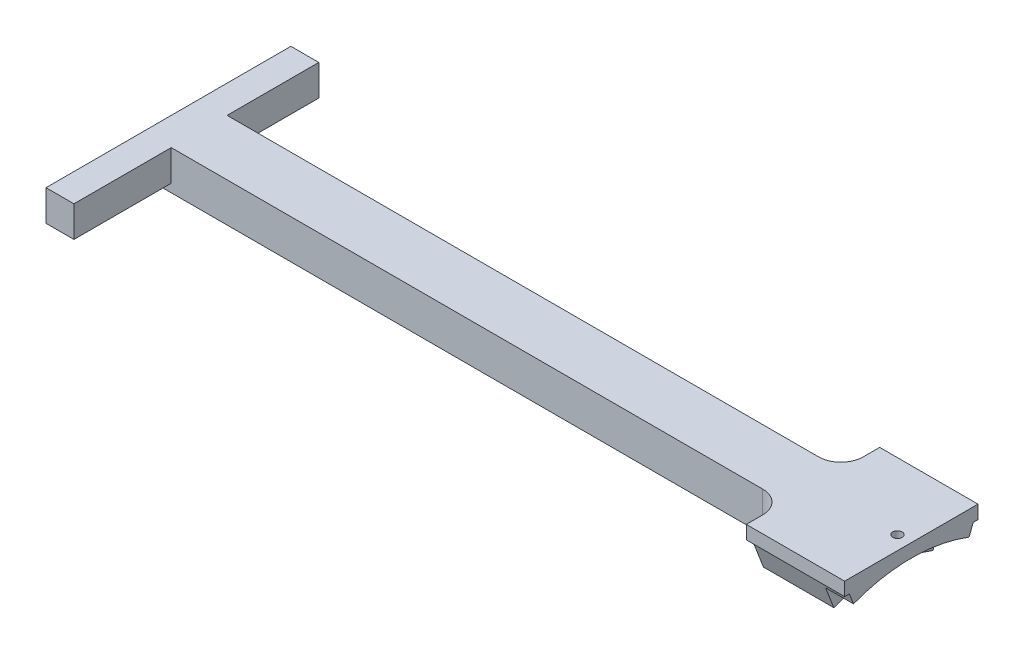
SolidWorks part; units mm, degrees
ref_plane "前视基准面" through (0, 0, 0) normal (0, 0, 1) x (1, 0, 0)
ref_plane "上视基准面" through (0, 0, 0) normal (0, 1, 0) x (1, 0, 0)
ref_plane "右视基准面" through (0, 0, 0) normal (1, 0, 0) x (0, 0, -1)
other "Configuration Table"
sketch "草图2" plane through (-10, 0, 0) normal (-1, 0, 0) x (0, 0, 1)
  line L0 (0, 0) -> (-20.629, 53.5702) construction
  line L2 (20.629, 53.5702) -> (0, 0) construction
  line L3 (0, 0) -> (0, 57.4049) construction
  arc A1 (20.629, 53.5702) -> (-20.629, 53.5702) centre (0, 0) ccw
  circle A2 centre (0, 0) radius 57.4049 construction
extrude "拉伸-薄壁1" add sketch "草图2" along normal blind 10 thin
sketch "草图3" plane through (-10, 0, 0) normal (1, 0, 0) x (0, 0, -1)
  arc A0 (22.4258, 58.2362) -> (-22.4258, 58.2362) centre (0, 0) ccw construction
  arc A1 (22.4258, 58.2362) -> (-22.4258, 58.2362) centre (0, 0) ccw
extrude "拉伸-薄壁2" add sketch "草图3" along normal blind 10 thin thin type one direction reverse wall 4.8
sketch "草图5" plane through (0, 0, 0) normal (1, 0, 0) x (0, 0, -1)
  line L0 (-23.8803, 62.4049) -> (23.8803, 62.4049)
  line L1 (0, 0) -> (0, 67.8698) construction
  arc A0 (22.4258, 58.2362) -> (-22.4258, 58.2362) centre (0, 0) ccw construction
extrude "拉伸-薄壁3" add sketch "草图5" against normal up to surface (20 mm away) thin
sketch "草图4" plane through (0, 0, 0) normal (0, 1, 0) x (1, 0, 0)
  circle A0 centre (-4.9601, 0) radius 1.55 construction
  circle A1 centre (-4.9601, 0) radius 1.55 construction
  circle A2 centre (-4.9601, 0) radius 1.7
  dimension "D1" = 0.15
extrude "切除-拉伸1" cut sketch "草图4" along normal through all
sketch "草图6" plane through (-20, 0, 0) normal (-1, 0, 0) x (0, 0, 1)
  line L7 (23.8803, 62.4049) -> (-23.8803, 62.4049)
  line L8 (-23.8803, 62.4049) -> (-23.8803, 57.6049)
  line L9 (-23.8803, 57.6049) -> (-22.1827, 57.6049)
  line L10 (-22.1827, 57.6049) -> (-17.7542, 46.1046)
  line L11 (17.7542, 46.1046) -> (22.1827, 57.6049)
  line L12 (22.1827, 57.6049) -> (23.8803, 57.6049)
  line L13 (23.8803, 57.6049) -> (23.8803, 62.4049)
  line L14 (23.8803, 62.4049) -> (-23.8803, 62.4049)
  line L15 (-23.8803, 62.4049) -> (-23.8803, 57.6049)
  line L16 (-23.8803, 57.6049) -> (-22.1827, 57.6049)
  line L17 (-22.1827, 57.6049) -> (-17.7542, 46.1046)
  line L18 (17.7542, 46.1046) -> (22.1827, 57.6049)
  line L19 (22.1827, 57.6049) -> (23.8803, 57.6049)
  line L20 (23.8803, 57.6049) -> (23.8803, 62.4049)
  arc A1 (17.7542, 46.1046) -> (-17.7542, 46.1046) centre (0, 0) ccw
  arc A2 (17.7542, 46.1046) -> (-17.7542, 46.1046) centre (0, 0) ccw
  dimension "D1" = 0
extrude "凸台-拉伸1" add sketch "草图6" along normal blind 245
sketch "草图7" plane through (0, 62.4049, 0) normal (0, 1, 0) x (1, 0, 0)
  line L0 (-35.2084, 23.8803) -> (-35.2084, 18)
  line L1 (-265, 23.8803) -> (0, 23.8803) construction
  line L2 (-43.2084, 10) -> (-265, 10)
  line L3 (-265, -23.8803) -> (-265, 23.8803) construction
  line L4 (-294, 0) -> (0, 0) construction
  line L5 (-43.2084, -10) -> (-265, -10)
  line L6 (-35.2084, -23.8803) -> (-35.2084, -18)
  line L7 (-265, 10) -> (-265, 23.8803)
  line L8 (-265, 23.8803) -> (-35.2084, 23.8803)
  line L9 (-35.2084, -23.8803) -> (-265, -23.8803)
  line L10 (-265, -23.8803) -> (-265, -10)
  arc A0 (-43.2084, 10) -> (-35.2084, 18) centre (-43.2084, 18) ccw
  arc A1 (-43.2084, -10) -> (-35.2084, -18) centre (-43.2084, -18) cw
  dimension "D1" = 8
  dimension "D2" = 10
extrude "切除-拉伸2" cut sketch "草图7" against normal through all
sketch "草图8" plane through (-265, 0, 0) normal (-1, 0, 0) x (0, 0, 1)
  line L0 (10, 62.4049) -> (-10, 62.4049) construction
  line L1 (-42.8355, 62.4049) -> (44.8485, 62.4049)
  line L2 (-42.8355, 62.4049) -> (-42.8355, 51.3444)
  line L3 (-42.8355, 51.3444) -> (44.8485, 51.3444)
  line L4 (44.8485, 62.4049) -> (44.8485, 51.3444)
extrude "凸台-拉伸2" add sketch "草图8" against normal blind 10
